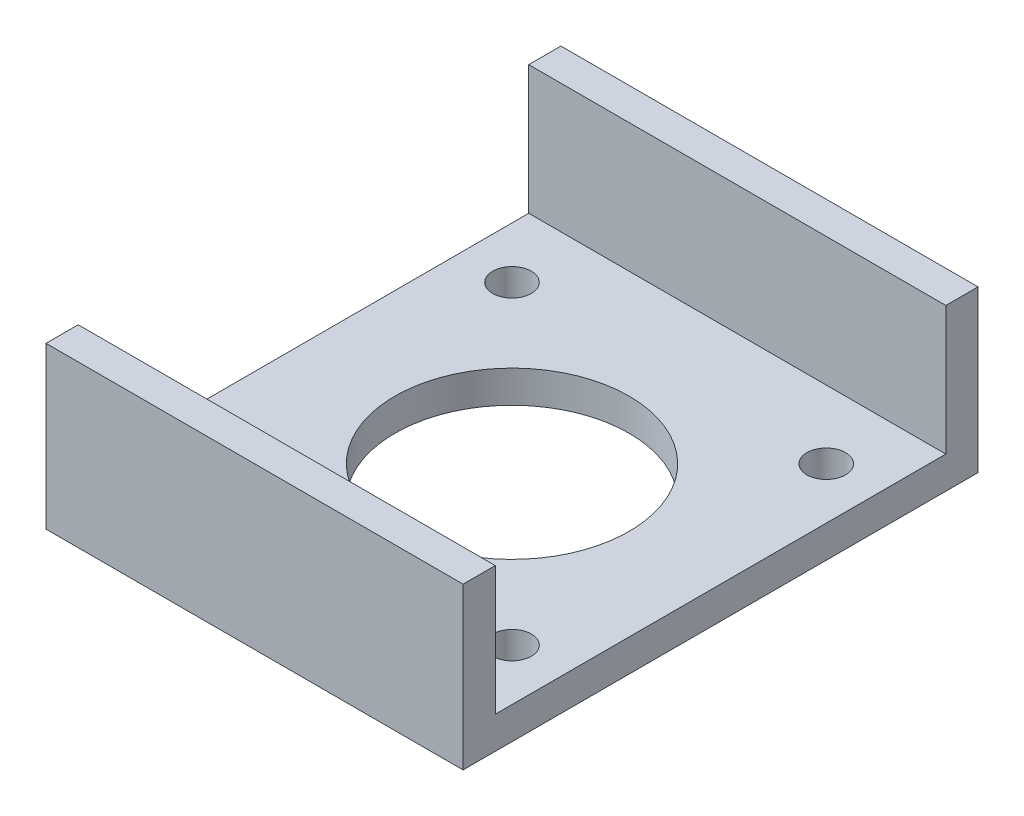
SolidWorks part; units mm, degrees
ref_plane "Front Plane" through (0, 0, 0) normal (0, 0, 1) x (1, 0, 0)
ref_plane "Top Plane" through (0, 0, 0) normal (0, 1, 0) x (1, 0, 0)
ref_plane "Right Plane" through (0, 0, 0) normal (1, 0, 0) x (0, 0, -1)
sketch "Sketch1" plane through (0, 0, 0) normal (0, 1, 0) x (1, 0, 0)
  line L5 (-15.5, -15.5) -> (15.5, -15.5) construction
  line L6 (-15.5, -15.5) -> (-15.5, 15.5) construction
  line L7 (-15.5, 15.5) -> (15.5, 15.5) construction
  line L8 (15.5, -15.5) -> (15.5, 15.5) construction
  line L9 (-15.5, -15.5) -> (15.5, 15.5) construction
  line L10 (-15.5, 15.5) -> (15.5, -15.5) construction
  line L11 (-20.574, -25.4) -> (20.574, -25.4)
  line L12 (-20.574, -25.4) -> (-20.574, 25.4)
  line L13 (-20.574, 25.4) -> (20.574, 25.4)
  line L14 (20.574, -25.4) -> (20.574, 25.4)
  line L15 (-20.574, -25.4) -> (20.574, 25.4) construction
  line L16 (-20.574, 25.4) -> (20.574, -25.4) construction
  circle A0 centre (0, 0) radius 11.557
  circle A1 centre (-15.5, 15.5) radius 1.905
  circle A2 centre (15.5, 15.5) radius 1.905
  circle A3 centre (15.5, -15.5) radius 1.905
  circle A4 centre (-15.5, -15.5) radius 1.905
  point P0 (0, 0)
  point P18 (0, 0)
  dimension "D2" = 23.114
  dimension "D3" = 3.81
  dimension "D1" = 31
  dimension "D5" = 50.8
  dimension "D6" = 41.148
  dimension "D4" = 4
extrude "Boss-Extrude1" add sketch "Sketch1" along normal blind 3.175
sketch "Sketch2" plane through (0, 3.175, 0) normal (0, 1, 0) x (1, 0, 0)
  line L0 (20.574, -25.4) -> (20.574, 25.4) construction
  line L1 (-20.574, -25.4) -> (20.574, -25.4)
  line L2 (-20.574, -25.4) -> (-20.574, -22.225)
  line L3 (-20.574, -22.225) -> (20.574, -22.225)
  line L4 (20.574, -25.4) -> (20.574, -22.225)
  line L5 (-20.574, 0) -> (20.574, 0) construction
  line L6 (-20.574, 25.4) -> (-20.574, -25.4) construction
  line L7 (20.574, 25.4) -> (20.574, 22.225)
  line L8 (-20.574, 22.225) -> (20.574, 22.225)
  line L9 (-20.574, 25.4) -> (-20.574, 22.225)
  line L10 (-20.574, 25.4) -> (20.574, 25.4)
  dimension "D1" = 3.175
extrude "Boss-Extrude2" add sketch "Sketch2" along normal blind 12.7
